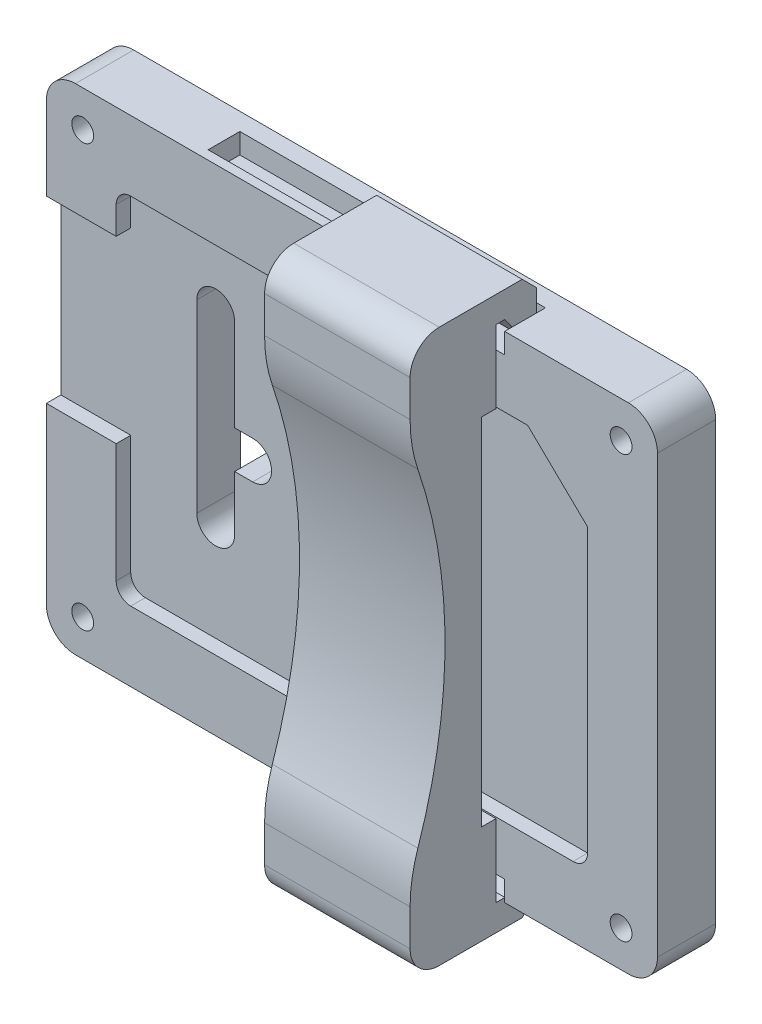
SolidWorks part; units mm, degrees
ref_plane "Ebene vorne" through (0, 0, 0) normal (0, 0, 1) x (1, 0, 0)
ref_plane "Ebene oben" through (0, 0, 0) normal (0, 1, 0) x (1, 0, 0)
ref_plane "Ebene rechts" through (0, 0, 0) normal (1, 0, 0) x (0, 0, -1)
sketch "Skizze1" plane through (0, 0, 0) normal (0, 0, 1) x (1, 0, 0)
  line L1 (0, 0) -> (-42, 0)
  line L2 (0, 0) -> (0, 34)
  line L3 (0, 34) -> (-42, 34)
  line L4 (-42, 0) -> (-42, 34)
  circle A0 centre (-39.5, 31.5) radius 0.75
  circle A1 centre (-2.5, 31.5) radius 0.75
  circle A2 centre (-39.5, 2.5) radius 0.75
  circle A3 centre (-2.5, 2.5) radius 0.75
  dimension "D3" = 1.5
  dimension "D1" = 42
  dimension "D2" = 34
extrude "Aufsatz-Linear austragen1" add sketch "Skizze1" along normal blind 4
ref_plane "Ebene1" through (0, 0, 3) normal (0, 0, 1) x (1, 0, 0)
sketch "Skizze2" plane through (0, 0, 3) normal (0, 0, 1) x (1, 0, 0)
  line L0 (-37, 29) -> (-37, 5) construction
  line L1 (-37, 5) -> (-5, 5) construction
  line L2 (-5, 5) -> (-5, 25.125) construction
  line L3 (-5, 25.125) -> (-9, 29) construction
  line L4 (-9, 29) -> (-37, 29) construction
  line L5 (-37.2, 29.2) -> (-37.2, 4.8)
  line L6 (-37.2, 4.8) -> (-4.8, 4.8)
  line L7 (-4.8, 4.8) -> (-4.8, 25.2097)
  line L8 (-4.8, 25.2097) -> (-8.919, 29.2)
  line L9 (-8.919, 29.2) -> (-37.2, 29.2)
  dimension "D1" = 32
  dimension "D2" = 24
  dimension "D3" = 4
  dimension "D4" = 3.875
  dimension "D5" = 5
  dimension "D6" = 5
  dimension "D7" = 0.2
extrude "Schnitt-Linear austragen1" cut sketch "Skizze2" along normal through all
sketch "Skizze3" plane through (0, 0, 0) normal (0, 0, 1) x (1, 0, 0)
  line L0 (-31.36, 24.3) -> (-31.36, 11.6) construction
  line L1 (-30.06, 24.3) -> (-30.06, 11.6)
  line L2 (-32.66, 24.3) -> (-32.66, 11.6)
  line L6 (-21.2, 24.3) -> (-21.2, 21.76) construction
  line L7 (-19.9, 24.3) -> (-19.9, 21.76)
  line L8 (-22.5, 24.3) -> (-22.5, 21.76)
  arc A10 (-30.06, 24.3) -> (-32.66, 24.3) centre (-31.36, 24.3) ccw
  arc A11 (-32.66, 11.6) -> (-30.06, 11.6) centre (-31.36, 11.6) ccw
  arc A14 (-19.9, 24.3) -> (-22.5, 24.3) centre (-21.2, 24.3) ccw
  arc A15 (-22.5, 21.76) -> (-19.9, 21.76) centre (-21.2, 21.76) ccw
  point P2 (-31.36, 17.95)
  point P14 (-21.2, 23.03)
  dimension "D1" = 1.3
extrude "Schnitt-Linear austragen2" cut sketch "Skizze3" along normal through all
sketch "Skizze5" plane through (0, 0, 0) normal (0, 0, 1) x (1, 0, 0)
  line L0 (-28.82, 16.68) -> (-31.36, 16.68) construction
  line L1 (-28.82, 15.38) -> (-31.36, 15.38)
  line L2 (-28.82, 17.98) -> (-31.36, 17.98)
  line L3 (-18.66, 21.76) -> (-21.2, 21.76) construction
  line L4 (-18.66, 20.46) -> (-21.2, 20.46)
  line L5 (-18.66, 23.06) -> (-21.2, 23.06)
  arc A0 (-28.82, 15.38) -> (-28.82, 17.98) centre (-28.82, 16.68) ccw
  arc A1 (-31.36, 17.98) -> (-31.36, 15.38) centre (-31.36, 16.68) ccw
  arc A2 (-18.66, 20.46) -> (-18.66, 23.06) centre (-18.66, 21.76) ccw
  arc A3 (-21.2, 23.06) -> (-21.2, 20.46) centre (-21.2, 21.76) ccw
  point P2 (-30.09, 16.68)
  point P7 (-19.93, 21.76)
  dimension "D1" = 1.3
extrude "Schnitt-Linear austragen4" cut sketch "Skizze5" along normal through all
sketch "Skizze4" plane through (0, 0, 3) normal (0, 0, 1) x (1, 0, 0)
  line L0 (-37.2, 29.2) -> (-37.2, 4.8) construction
  line L1 (-37.2, 13.9675) -> (-42.3863, 13.9675)
  line L2 (-37.2, 13.9675) -> (-37.2, 26.3056)
  line L3 (-37.2, 26.3056) -> (-42.3863, 26.3056)
  line L4 (-42.3863, 13.9675) -> (-42.3863, 26.3056)
extrude "Schnitt-Linear austragen3" cut sketch "Skizze4" along normal through all
fillet "Verrundung1" radius 2 4 edges at (0, 34, 2) (-42, 34, 2) (-42, 0, 2) (0, 0, 2)
fillet "Verrundung2" radius 1 3 edges at (-4.8, 4.8, 3.5) (-37.2, 4.8, 3.5) (-37.2, 29.2, 3.5)
chamfer "Fase2" distance 0.5 angle 45 4 edges at (-1.75, 31.5, 0) (-1.75, 2.5, 0) (-38.75, 31.5, 0) (-38.75, 2.5, 0)
ref_plane "Ebene2" through (-21, 0, 0) normal (1, 0, 0) x (0, 0, -1)
sketch "Skizze14" plane through (-21, 0, 0) normal (1, 0, 0) x (0, 0, -1)
  line L0 (-4, 34) -> (0, 34) construction
  line L1 (-3.3803, 34) -> (-1.2, 34)
  line L3 (-2.4, 32.6) -> (-1.2, 32.6)
  line L4 (-1.2, 34) -> (-1.2, 32.6)
  line L10 (-2.4, 32.6) -> (-3.3803, 34)
  dimension "D1" = 125
  dimension "D2" = 1.2
  dimension "D3" = 1.4
  dimension "D4" = 1.2
extrude "Schnitt-Linear austragen8" cut sketch "Skizze14" against normal mid plane 21
sketch "Skizze15" plane through (-21, 0, 0) normal (1, 0, 0) x (0, 0, -1)
  line L1 (-1.2, 32.6) -> (-5.238, 32.6)
  line L2 (-1.2, 32.6) -> (-1.2, 34.2392)
  line L3 (-1.2, 34.2392) -> (-5.238, 34.2392)
  line L4 (-5.238, 32.6) -> (-5.238, 34.2392)
extrude "Schnitt-Linear austragen9" cut sketch "Skizze15" along normal up to surface (10.5 mm away) up to face at (-10.5, 33.3, 2.0451)
ref_plane "Ebene4" through (0, 17, 0) normal (0, 1, 0) x (1, 0, 0)
mirror "Spiegeln2" about plane through (0, 17, 0) normal (0, 1, 0) of "Schnitt-Linear austragen8", "Schnitt-Linear austragen9"
sketch "Skizze16" plane through (-21, 0, 0) normal (1, 0, 0) x (0, 0, -1)
  line L0 (-4.1, 34.2) -> (-3.4803, 34.2)
  line L1 (-1.3, 32.8) -> (-1.3, 36)
  line L2 (-1.3, 36) -> (-10, 36)
  line L3 (-5.1, 29.2) -> (-5.1, 17)
  line L4 (-3.4803, 34.2) -> (-2.5, 32.8)
  line L5 (-2.5, 32.8) -> (-1.3, 32.8)
  line L6 (5.5, 17) -> (-5.5, 17) construction
  line L7 (-10, 36) -> (-10, 29.7373)
  line L8 (-5.1, 17) -> (-7.6, 17)
  line L9 (-7.6, 17) -> (-7.6, 15.0556) construction
  line L10 (-4.1, 34.2) -> (-4.1, 29.2)
  line L11 (-4.1, 29.2) -> (-5.1, 29.2)
  arc A0 (-10, 29.7373) -> (-7.6, 17) centre (-42.6, 17) cw
  dimension "D9" = 35
  dimension "D1" = 5.1
  dimension "D2" = 1.3
  dimension "D3" = 32.8
  dimension "D4" = 125
  dimension "D5" = 1.2
  dimension "D6" = 34.2
  dimension "D7" = 10
  dimension "D8" = 2.5
  dimension "D10" = 36
  dimension "D11" = 4.1
  dimension "D12" = 29.2
extrude "Aufsatz-Linear austragen5" add sketch "Skizze16" along normal blind 10 separate body
chamfer "Fase4" distance 1 angle 45 1 edges at (-16, 36, 1.3)
fillet "Verrundung10" radius 2 1 edges at (-16, 36, 10)
fillet "Verrundung11" radius 10 1 edges at (-16, 29.7373, 10)
mirror "Spiegeln3" about plane through (0, 17, 0) normal (0, 1, 0) of bodies 117
